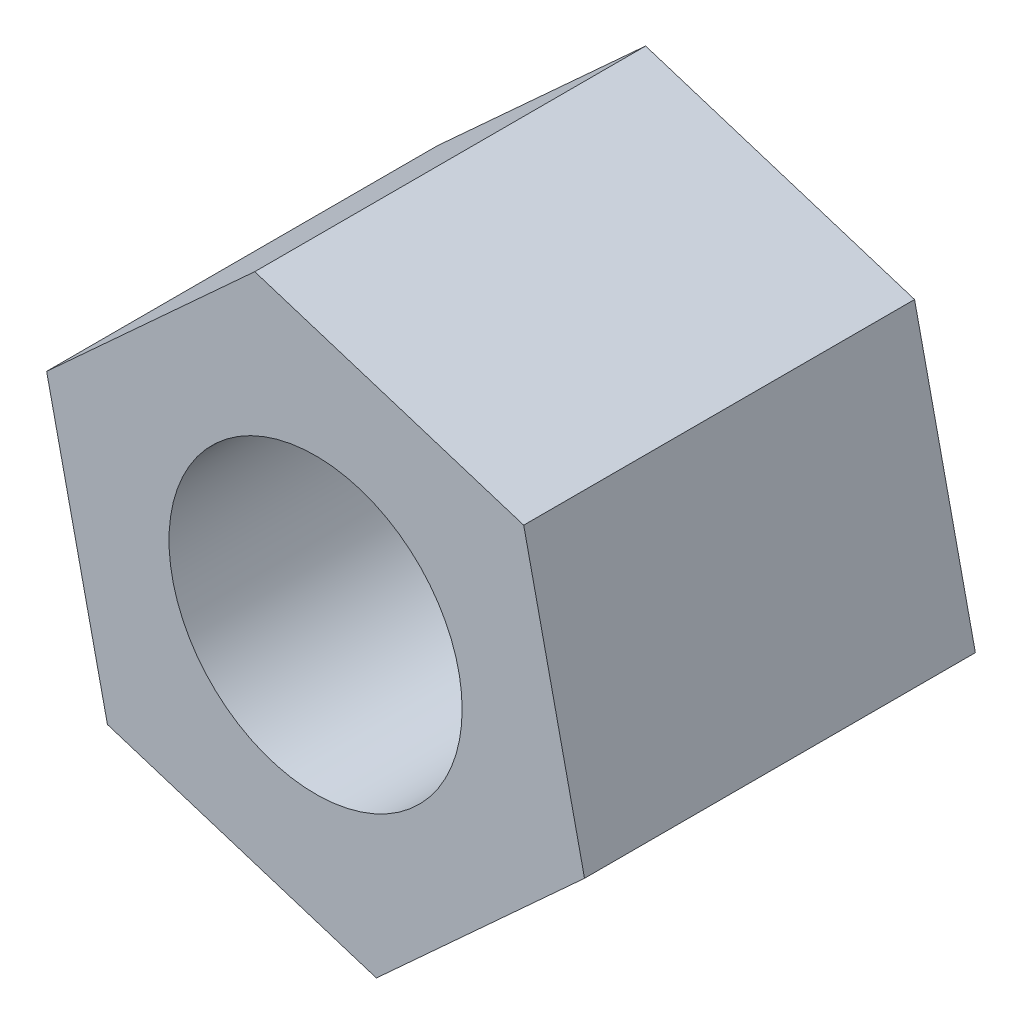
SolidWorks part; units mm, degrees
ref_plane "前视基准面" through (0, 0, 0) normal (0, 0, 1) x (1, 0, 0)
ref_plane "上视基准面" through (0, 0, 0) normal (0, 1, 0) x (1, 0, 0)
ref_plane "右视基准面" through (0, 0, 0) normal (1, 0, 0) x (0, 0, -1)
sketch "草图1" plane through (0, 0, 0) normal (0, 0, 1) x (1, 0, 0)
  line L1 (-0.6223, 2.8189) -> (-2.7524, 0.8705)
  line L2 (-2.7524, 0.8705) -> (-2.13, -1.9484)
  line L3 (-2.13, -1.9484) -> (0.6223, -2.8189)
  line L4 (0.6223, -2.8189) -> (2.7524, -0.8705)
  line L5 (2.7524, -0.8705) -> (2.13, 1.9484)
  line L6 (2.13, 1.9484) -> (-0.6223, 2.8189)
  circle A0 centre (0, 0) radius 2.5 construction
  circle A1 centre (0, 0) radius 1.5
  dimension "D2" = 3
  dimension "D1" = 5
extrude "凸台-拉伸1" add sketch "草图1" along normal blind 4
